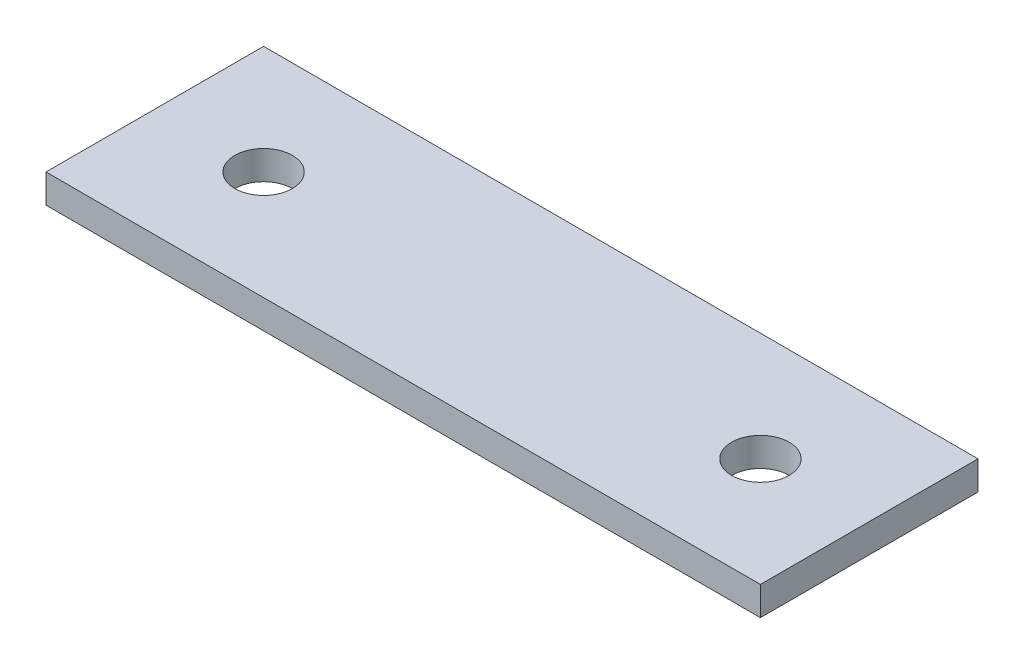
SolidWorks part; units mm, degrees
ref_plane "Front Plane" through (0, 0, 0) normal (0, 0, 1) x (1, 0, 0)
ref_plane "Top Plane" through (0, 0, 0) normal (0, 1, 0) x (1, 0, 0)
ref_plane "Right Plane" through (0, 0, 0) normal (1, 0, 0) x (0, 0, -1)
sketch "Sketch1" plane through (0, 0, 0) normal (0, 1, 0) x (1, 0, 0)
  line L0 (-13.7, 0) -> (13.7, 0) construction
  line L1 (19.7, -6) -> (-19.7, -6)
  line L2 (19.7, -6) -> (19.7, 6)
  line L3 (19.7, 6) -> (-19.7, 6)
  line L4 (-19.7, -6) -> (-19.7, 6)
  line L5 (19.7, -6) -> (-19.7, 6) construction
  line L6 (19.7, 6) -> (-19.7, -6) construction
  circle A0 centre (-13.7, 0) radius 1.5875
  circle A1 centre (13.7, 0) radius 1.5875
  circle A2 centre (-13.7, 0) radius 5 construction
  point P0 (0, 0)
  point P8 (0, 0)
  dimension "D1" = 3.175
  dimension "D4" = 10
  dimension "D2" = 27.4
  dimension "D3" = 12
  dimension "D5" = 6
extrude "Boss-Extrude1" add sketch "Sketch1" along normal mid plane 1.5875
